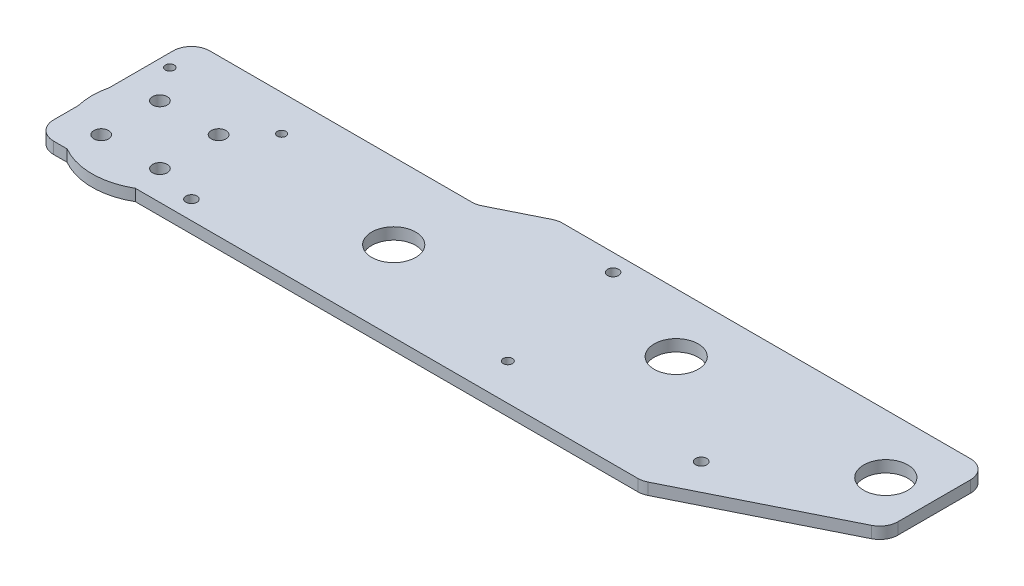
SolidWorks part; units mm, degrees
ref_plane "Front" through (0, 0, 0) normal (0, 0, 1) x (1, 0, 0)
ref_plane "Top" through (0, 0, 0) normal (0, 1, 0) x (1, 0, 0)
ref_plane "Right" through (0, 0, 0) normal (1, 0, 0) x (0, 0, -1)
sketch "Sketch1" plane through (0, 0, 0) normal (0, 1, 0) x (1, 0, 0)
  line L1 (0, 0) -> (210, 0)
  line L2 (0, 0) -> (0, -50)
  line L3 (0, -50) -> (210, -50)
  line L4 (210, 0) -> (210, -50)
  circle A7 centre (3.4895, -16.7877) radius 1.2117
  circle A8 centre (34.3726, -17.194) radius 1.1656
  circle A9 centre (37.5207, -44.9212) radius 1.5
  circle A10 centre (118.879, -40.0177) radius 1.25
  circle A11 centre (112.3021, -4.7393) radius 1.5
  circle A12 centre (168.9752, -37.4032) radius 1.5173
  dimension "D1" = 210
  dimension "D2" = 50
extrude "Boss-Extrude1" add sketch "Sketch1" along normal blind 3.175
sketch "Sketch2" plane through (0, 3.175, 0) normal (0, 1, 0) x (1, 0, 0)
  line L0 (210, 0) -> (0, 0) construction
  line L1 (0, 0) -> (0, -50) construction
  circle A0 centre (10, -26) radius 2
  circle A1 centre (10, -42) radius 2
  circle A2 centre (26, -26) radius 2
  circle A3 centre (26, -42) radius 2
  dimension "D1" = 16
  dimension "D2" = 16
  dimension "D3" = 16
  dimension "D4" = 26
  dimension "D5" = 10
  dimension "D6" = 10
  dimension "D7" = 26
  dimension "D8" = 16
extrude "Cut-Extrude1" cut sketch "Sketch2" against normal blind 10
sketch "Sketch3" plane through (0, 3.175, 0) normal (0, 1, 0) x (1, 0, 0)
  line L0 (210, 0) -> (0, 0) construction
  circle A0 centre (75.8499, -28.1) radius 6
  circle A1 centre (140.772, -16) radius 6
  circle A2 centre (18, -34) radius 0.587
  circle A3 centre (26, -26) radius 2 construction
  circle A4 centre (197.922, -16) radius 6
  dimension "D1" = 28.1
  dimension "D3" = 66.04
  dimension "D4" = 16
  dimension "D7" = 57.15
  dimension "D2" = 58.15
  dimension "D5" = 8
  dimension "D6" = 8
extrude "Cut-Extrude2" cut sketch "Sketch3" against normal blind 57.15
sketch "Sketch4" [suppressed] plane through (0, 3.175, 0) normal (0, 1, 0) x (1, 0, 0)
  line L0 (3.4895, -16.7877) -> (18, -34)
  line L1 (3.4895, -20.6627) -> (5.9498, -23.5811)
  line L2 (18, -34) -> (34.3726, -17.194)
  line L3 (34.3726, -17.194) -> (75.8499, -28.1)
  line L4 (75.8499, -28.1) -> (37.5207, -44.9212)
  line L5 (7.3432, -17.194) -> (9.8664, -20.303)
  circle A0 centre (18, -34) radius 15.9299
  circle A1 centre (3.4895, -16.7877) radius 3.8751
  circle A2 centre (34.3726, -17.194) radius 3.7227
  circle A3 centre (37.5207, -44.9212) radius 3.8676
  circle A4 centre (75.8499, -28.1) radius 12.797
  circle A5 centre (112.3021, -4.7393) radius 5.1588
  circle A6 centre (118.879, -40.0177) radius 4.9035
  circle A7 centre (140.772, -16) radius 12.6375
  circle A8 centre (168.9752, -37.4032) radius 4.2066
  circle A9 centre (197.922, -16) radius 12.8
sketch "Sketch5" [suppressed] plane through (0, 3.175, 0) normal (0, 1, 0) x (1, 0, 0)
  line L0 (210, 0) -> (0, 0) construction
  line L2 (-0.6266, -16.7877) -> (37.5207, -16.7877)
  line L3 (-0.6266, -16.7877) -> (-0.6266, -44.9212)
  line L4 (-0.6266, -44.9212) -> (37.5207, -44.9212)
  line L5 (37.5207, -16.7877) -> (37.5207, -44.9212)
  line L6 (75.8499, -15.182) -> (37.5207, -15.182)
  line L7 (75.8499, -15.182) -> (75.8499, -44.9212)
  line L8 (75.8499, -44.9212) -> (37.5207, -44.9212)
  line L9 (37.5207, -15.182) -> (37.5207, -44.9212)
  line L10 (112.3021, -4.7393) -> (75.8499, -4.7393)
  line L11 (112.3021, -4.7393) -> (112.3021, -44.9212)
  line L12 (112.3021, -44.9212) -> (75.8499, -44.9212)
  line L13 (75.8499, -4.7393) -> (75.8499, -44.9212)
  line L14 (112.3021, -4.7393) -> (102.3945, -4.7393)
  line L16 (112.3021, -4.7393) -> (112.3021, 0)
  line L17 (112.3021, 0) -> (102.3945, 0)
  line L18 (102.3945, -4.7393) -> (102.3945, 0)
  line L19 (210, -50) -> (210, 0) construction
  line L20 (112.3021, -4.7393) -> (123.1553, -4.7393)
  line L21 (112.3021, -4.7393) -> (112.3021, 0)
  line L22 (112.3021, 0) -> (123.1553, 0)
  line L23 (123.1553, -4.7393) -> (123.1553, 0)
  line L24 (112.3021, -4.7393) -> (140.772, -4.7393)
  line L25 (112.3021, -4.7393) -> (112.3021, -40.0177)
  line L26 (112.3021, -40.0177) -> (140.772, -40.0177)
  line L27 (140.772, -4.7393) -> (140.772, -40.0177)
  line L28 (140.772, -16) -> (168.9752, -16)
  line L29 (140.772, -16) -> (140.772, -40.0177)
  line L30 (140.772, -40.0177) -> (168.9752, -40.0177)
  line L31 (168.9752, -16) -> (168.9752, -40.0177)
  line L32 (168.9752, -4.7393) -> (210, -4.7393)
  line L33 (168.9752, -4.7393) -> (168.9752, -40.0177)
  line L34 (168.9752, -40.0177) -> (210, -40.0177)
  line L35 (210, -4.7393) -> (210, -40.0177)
  line L36 (0, -50) -> (210, -50) construction
  line L37 (160.7629, -40.0177) -> (177.2091, -40.0177)
  line L38 (160.7629, -40.0177) -> (160.7629, -44.9212)
  line L39 (160.7629, -44.9212) -> (177.2091, -44.9212)
  line L40 (177.2091, -40.0177) -> (177.2091, -44.9212)
  line L41 (112.3021, -40.0177) -> (126.3591, -40.0177)
  line L42 (112.3021, -40.0177) -> (112.3021, -47.7828)
  line L43 (112.3021, -47.7828) -> (126.3591, -47.7828)
  line L44 (126.3591, -40.0177) -> (126.3591, -47.7828)
  line L45 (30.5963, -44.9212) -> (44.6115, -44.9212)
  line L46 (30.5963, -44.9212) -> (30.5963, -50)
  line L47 (30.5963, -50) -> (44.6115, -50)
  line L48 (44.6115, -44.9212) -> (44.6115, -50)
  line L50 (-0.6266, -44.9212) -> (30.5963, -44.9212)
  line L51 (-0.6266, -44.9212) -> (-0.6266, -50)
  line L52 (-0.6266, -50) -> (30.5963, -50)
  line L53 (30.5963, -44.9212) -> (30.5963, -50)
  circle A0 centre (3.4895, -16.7877) radius 4.1161
  circle A1 centre (34.3726, -17.194) radius 3.8132
  circle A2 centre (75.8499, -28.1) radius 12.918
  circle A3 centre (112.3021, -4.7393) radius 5.2663
  circle A4 centre (140.772, -16) radius 13.0245
  circle A5 centre (197.922, -16) radius 12.3805
  circle A6 centre (168.9752, -37.4032) radius 4.7643
  circle A7 centre (118.879, -40.0177) radius 5.279
  circle A8 centre (37.5207, -44.9212) radius 4.2049
  line M12 (0, 0) -> (0, -50)
  line M13 (0, -50) -> (210, -50)
  line M14 (210, -50) -> (210, 0)
  line M15 (210, 0) -> (0, 0)
extrude "Cut-Extrude5" [suppressed] cut sketch "Sketch5" against normal blind 11.52 contours A5 L32 L23 L24 A4 L28 L33 M14 M15 | A1 L6 L13 L10 L18 A0 L2 M15 M12 | L8 L48 L34 L40 L39 L38 L30 L26 L44 L43 L42 L12 M13 M14
fillet "Fillet1" [suppressed] radius 5
sketch "Sketch10" plane through (0, 3.175, 0) normal (0, 1, 0) x (1, 0, 0)
  line L0 (210, -27.8594) -> (165.5029, -50)
  line L1 (210, -50) -> (210, 0) construction
  line L2 (0, -50) -> (210, -50) construction
  line L3 (165.5029, -50) -> (210, -50)
  line L4 (210, -50) -> (210, -27.8594)
  line L5 (92.5326, 0) -> (77.6548, -7.4028)
  line L6 (210, 0) -> (0, 0) construction
  line L7 (77.6548, -7.4028) -> (0, -7.4028)
  line L8 (0, 0) -> (0, -50) construction
  line L9 (0, -7.4028) -> (0, 0)
  line L10 (0, 0) -> (92.5326, 0)
extrude "Cut-Extrude7" cut sketch "Sketch10" against normal blind 10
fillet "Fillet3" radius 5 7 edges at (0, 1.5875, 50) (0, 1.5875, 7.4028) (77.6548, 1.5875, 7.4028) (92.5326, 1.5875, 0) (210, 1.5875, 0) (210, 1.5875, 27.8594) (165.5029, 1.5875, 50)
sketch "Sketch11" plane through (0, 3.175, 0) normal (0, 1, 0) x (1, 0, 0)
  circle A0 centre (18, -34) radius 18.5
  circle A1 centre (10, -26) radius 2
  circle A2 centre (10, -42) radius 2
  circle A3 centre (26, -26) radius 2
  circle A4 centre (26, -42) radius 2
extrude "Boss-Extrude4" add sketch "Sketch11" against normal blind 3.175
